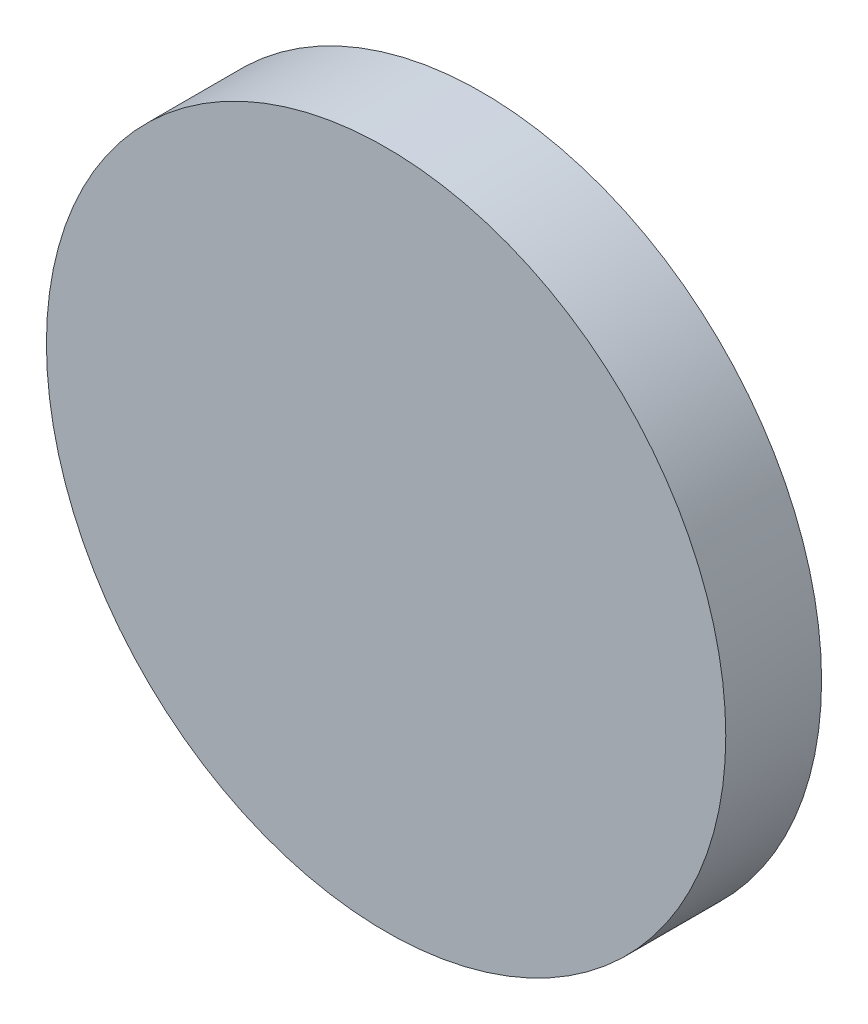
SolidWorks part; units mm, degrees
material "普通碳钢"
ref_plane "前视基准面" through (0, 0, 0) normal (0, 0, 1) x (1, 0, 0)
ref_plane "上视基准面" through (0, 0, 0) normal (0, 1, 0) x (1, 0, 0)
ref_plane "右视基准面" through (0, 0, 0) normal (1, 0, 0) x (0, 0, -1)
sketch "草图1" plane through (0, 0, 0) normal (0, 0, 1) x (1, 0, 0)
  circle A0 centre (0, 0) radius 35.4558
extrude "凸台-拉伸1" add sketch "草图1" along normal blind 10
